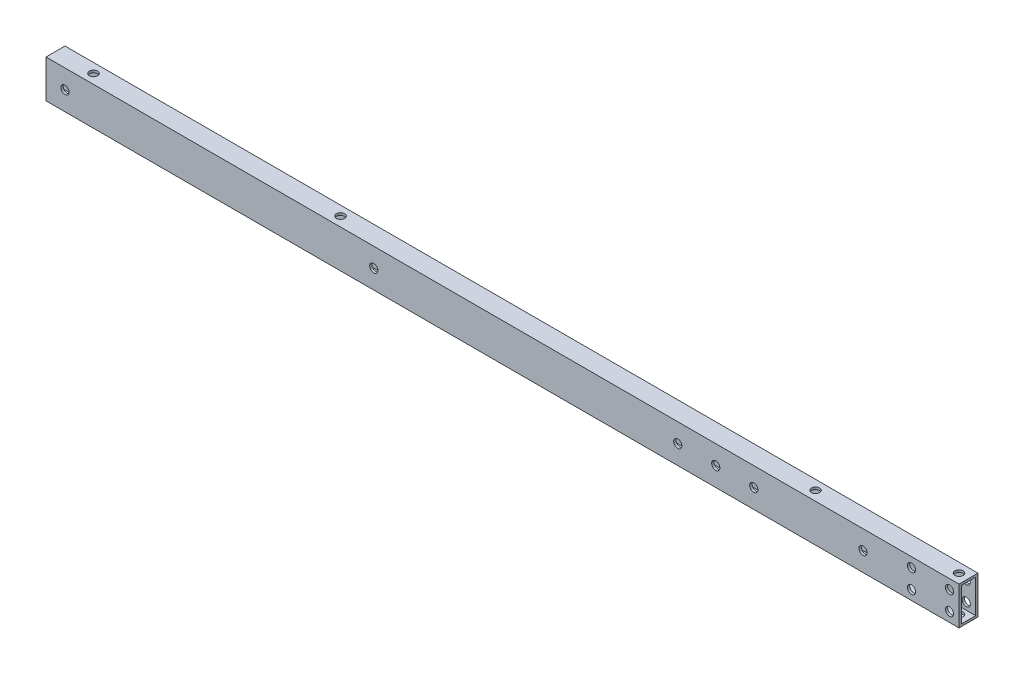
SolidWorks part; units mm, degrees
material "5052-H34"
ref_plane "正面" through (0, 0, 0) normal (0, 0, 1) x (1, 0, 0)
ref_plane "平面" through (0, 0, 0) normal (0, 1, 0) x (1, 0, 0)
ref_plane "右側面" through (0, 0, 0) normal (1, 0, 0) x (0, 0, -1)
sketch "ｽｹｯﾁ1" plane through (0, 0, 0) normal (1, 0, 0) x (0, 0, -1)
  line L1 (-5, 10) -> (5, 10)
  line L2 (-5, 10) -> (-5, -10)
  line L3 (-5, -10) -> (5, -10)
  line L4 (5, 10) -> (5, -10)
  line L5 (-5, 10) -> (5, -10) construction
  line L6 (-5, -10) -> (5, 10) construction
  point P0 (0, 0)
  dimension "D1" = 10
  dimension "D2" = 20
extrude "押し出し-薄板1" add sketch "ｽｹｯﾁ1" along normal blind 480.5 thin
sketch "ｽｹｯﾁ2" plane through (0, 0, 5) normal (0, 0, 1) x (1, 0, 0)
  line L0 (352.5, 10) -> (352.5, -10) construction
  line L1 (480.5, 0) -> (430, 0) construction
  line L3 (352.5, 0) -> (372.5, 0) construction
  line L4 (0, 0) -> (10, 0) construction
  line L5 (480.5, 10) -> (0, 10) construction
  line L6 (480.5, 10) -> (480.5, -10) construction
  line L7 (352.5, 0) -> (172.5, 0) construction
  circle A0 centre (372.5, 0) radius 2.15
  circle A1 centre (332.5, 0) radius 2.15
  circle A2 centre (352.5, 0) radius 2.15
  circle A5 centre (172.5, 0) radius 2.15
  circle A7 centre (10, 0) radius 2.15
  circle A8 centre (475.5, 5) radius 2.15
  circle A10 centre (475.5, -5) radius 2.15
  circle A11 centre (455.5, 5) radius 2.15
  circle A12 centre (455.5, -5) radius 2.15
  circle A13 centre (430, 0) radius 2.15
  dimension "D2" = 4.3
  dimension "D3" = 4.3
  dimension "D4" = 10
  dimension "D9" = 4.3
  dimension "D6" = 4.3
  dimension "D11" = 5
  dimension "D12" = 20
  dimension "D14" = 4.3
  dimension "D1" = 40
  dimension "D5" = 128
  dimension "D7" = 5
  dimension "D8" = 10
  dimension "D10" = 180
  dimension "D13" = 50.5
extrude "ｶｯﾄ - 押し出し1" cut sketch "ｽｹｯﾁ2" against normal through all
sketch "ｽｹｯﾁ3" plane through (0, 10, 0) normal (0, 1, 0) x (1, 0, 0)
  line L1 (0, 0) -> (150, 0) construction
  line L3 (480.5, 5) -> (480.5, -5) construction
  line L6 (480.5, 0) -> (475.5, 0) construction
  circle A0 centre (400, 0) radius 2.15
  circle A2 centre (475.5, 0) radius 2.15
  circle A4 centre (150, 0) radius 2.15
  circle A5 centre (20, 0) radius 2.15
  dimension "D2" = 4.3
  dimension "D5" = 5
  dimension "D4" = 4.3
  dimension "D6" = 80.5
  dimension "D7" = 4.3
  dimension "D1" = 250
  dimension "D3" = 130
extrude "ｶｯﾄ - 押し出し2" cut sketch "ｽｹｯﾁ3" against normal through all
